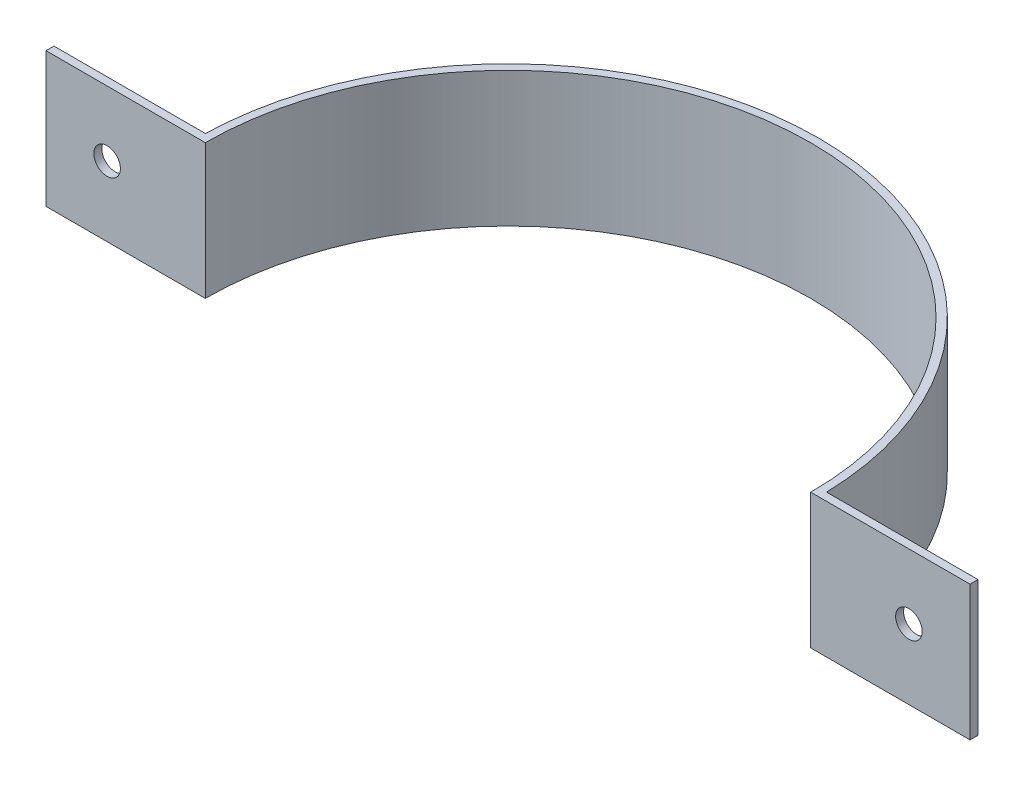
SolidWorks part; units mm, degrees
material "PVC Rígido"
ref_plane "Alzado" through (0, 0, 0) normal (0, 0, 1) x (1, 0, 0)
ref_plane "Planta" through (0, 0, 0) normal (0, 1, 0) x (1, 0, 0)
ref_plane "Vista lateral" through (0, 0, 0) normal (1, 0, 0) x (0, 0, -1)
sketch "Croquis1" plane through (0, 0, 0) normal (0, 1, 0) x (1, 0, 0)
  line L0 (-58.5, 0) -> (-57, 0)
  line L1 (57, 0) -> (58.5, 0)
  arc A0 (57, 0) -> (-57, 0) centre (0, 0) ccw
  arc A1 (58.5, 0) -> (-58.5, 0) centre (0, 0) ccw
  dimension "D1" = 114
  dimension "D2" = 117
extrude "Saliente-Extruir1" add sketch "Croquis1" along normal blind 25.4
sketch "Croquis2" plane through (0, 0, 0) normal (0, 0, 1) x (1, 0, 0)
  line L0 (57, 25.4) -> (87, 25.4)
  line L1 (87, 25.4) -> (87, 0)
  line L2 (87, 0) -> (57, 0)
  line L3 (57, 0) -> (57, 25.4)
  line L4 (-57, 25.4) -> (-57, 0) construction
  line L5 (-57, 0) -> (-87, 0)
  line L6 (-57, 0) -> (-57, 25.4)
  line L7 (-57, 25.4) -> (-87, 25.4)
  line L8 (-87, 0) -> (-87, 25.4)
  point P2 (0, 0)
  dimension "D1" = 30
extrude "Saliente-Extruir2" add sketch "Croquis2" against normal blind 1.5
sketch "Croquis4" plane through (0, 0, -1.5) normal (0, 0, -1) x (-1, 0, 0)
  line L1 (-87, 0) -> (-87, 25.4) construction
  line L3 (87, 25.4) -> (87, 0) construction
  circle A0 centre (75.49, 13.1643) radius 2.5
  circle A1 centre (-75.49, 13.1643) radius 2.5
  dimension "D1" = 5
  dimension "D2" = 5
  dimension "D3" = 11.51
  dimension "D4" = 11.51
extrude "Cortar-Extruir1" cut sketch "Croquis4" against normal blind 10
